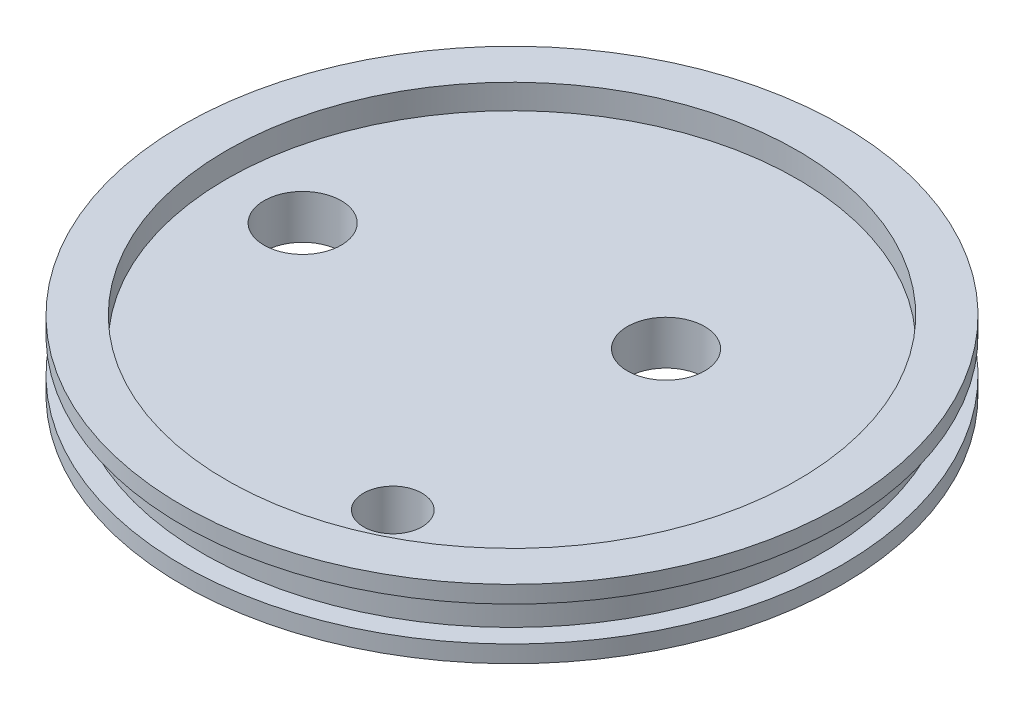
SolidWorks part; units mm, degrees
material "6061-T6 (SS)"
ref_plane "Front Plane" through (0, 0, 0) normal (0, 0, 1) x (1, 0, 0)
ref_plane "Top Plane" through (0, 0, 0) normal (0, 1, 0) x (1, 0, 0)
ref_plane "Right Plane" through (0, 0, 0) normal (1, 0, 0) x (0, 0, -1)
sketch "Sketch1" plane through (0, 0, 0) normal (0, 0, 1) x (1, 0, 0)
  line L0 (0, 48.1922) -> (0, -25.6743) construction
  line L1 (0, 0) -> (47.498, 0)
  line L2 (47.498, 0) -> (47.498, 2.4638)
  line L3 (47.498, 2.4638) -> (44.577, 2.4638)
  line L4 (44.577, 2.4638) -> (44.577, 7.4422)
  line L5 (44.577, 7.4422) -> (47.498, 7.4422)
  line L6 (47.498, 7.4422) -> (47.498, 9.906)
  line L7 (47.498, 9.906) -> (41.148, 9.906)
  line L8 (41.148, 9.906) -> (41.148, 6.35)
  line L9 (41.148, 6.35) -> (0, 6.35)
  line L10 (0, 6.35) -> (0, 0)
  dimension "D1" = 94.996
  dimension "D2" = 4.9784
  dimension "D3" = 2.921
  dimension "D4" = 9.906
  dimension "D5" = 6.35
  dimension "D6" = 6.35
revolve "Revolve1" add sketch "Sketch1" angle 360 about L0
hole_wizard "Pipe Tap Drill for 1/4 Tap1" positions "Sketch2" profile "Sketch3" hole size "1/4" standard "ANSI Inch" end condition through all
sketch "Sketch2" plane through (0, 6.35, 0) normal (0, 1, 0) x (1, 0, 0)
  point P0 (0, 0)
  point P4 (-30.1752, 0)
  dimension "D1" = 30.1752
sketch "Sketch3" plane through (0, 6.35, 0) normal (1, 0, 0) x (0, 0, 1)
  line L0 (0, 0) -> (0, 6.35)
  line L1 (0, 6.35) -> (5.5626, 6.35)
  line L2 (5.5626, 6.35) -> (5.5626, 0)
  line L5 (5.5626, 0) -> (0, 0)
  line L11 (0, -6.35) -> (0, 107.95) construction
  dimension "Thru Hole Dia." = 11.1252
  dimension "Thru Hole Depth" = 6.35
hole_wizard "Pipe Tap Drill for 1/8 Tap1" positions "Sketch4" profile "Sketch5" hole size "1/8" standard "ANSI Inch" end condition through all
sketch "Sketch4" plane through (0, 6.35, 0) normal (0, 1, 0) x (1, 0, 0)
  line L0 (0, 0) -> (12.1502, -29.3332)
  line L1 (0, 0) -> (0, -37.3592)
  point P16 (12.1502, -29.3332)
  dimension "D1" = 31.75
  dimension "D2" = 22.5
sketch "Sketch5" plane through (12.1502, 6.35, 29.3332) normal (1, 0, 0) x (0, 0, 1)
  line L0 (0, 0) -> (0, 6.35)
  line L1 (0, 6.35) -> (4.2164, 6.35)
  line L2 (4.2164, 6.35) -> (4.2164, 0)
  line L5 (4.2164, 0) -> (0, 0)
  line L11 (0, -6.35) -> (0, 107.95) construction
  dimension "Thru Hole Dia." = 8.4328
  dimension "Thru Hole Depth" = 6.35
sketch "Sketch6" plane through (0, 6.35, 0) normal (0, 1, 0) x (1, 0, 0)
  circle A0 centre (0, 0) radius 6.35
  dimension "D1" = 12.7
extrude "Boss-Extrude1" add sketch "Sketch6" against normal blind 6.35
sketch "Sketch7" plane through (0, 6.35, 0) normal (0, 1, 0) x (1, 0, 0)
  point P0 (11.7143, 10.4859)
hole_wizard "Pipe Tap Drill for 1/4 Tap2" positions "Sketch10" profile "Sketch9" hole size "1/4" standard "ANSI Inch" end condition up to next
sketch "Sketch10" plane through (0, 6.35, 0) normal (0, 1, 0) x (1, 0, 0)
  point P0 (11.7143, 10.4859)
sketch "Sketch9" plane through (11.7143, 6.35, -10.4859) normal (1, 0, 0) x (0, 0, 1)
  line L0 (0, 0) -> (0, 6.35)
  line L1 (0, 6.35) -> (5.5626, 6.35)
  line L2 (5.5626, 6.35) -> (5.5626, 0)
  line L5 (5.5626, 0) -> (0, 0)
  line L11 (0, -6.35) -> (0, 107.95) construction
  dimension "Thru Hole Dia." = 11.1252
  dimension "Thru Hole Depth" = 6.35
